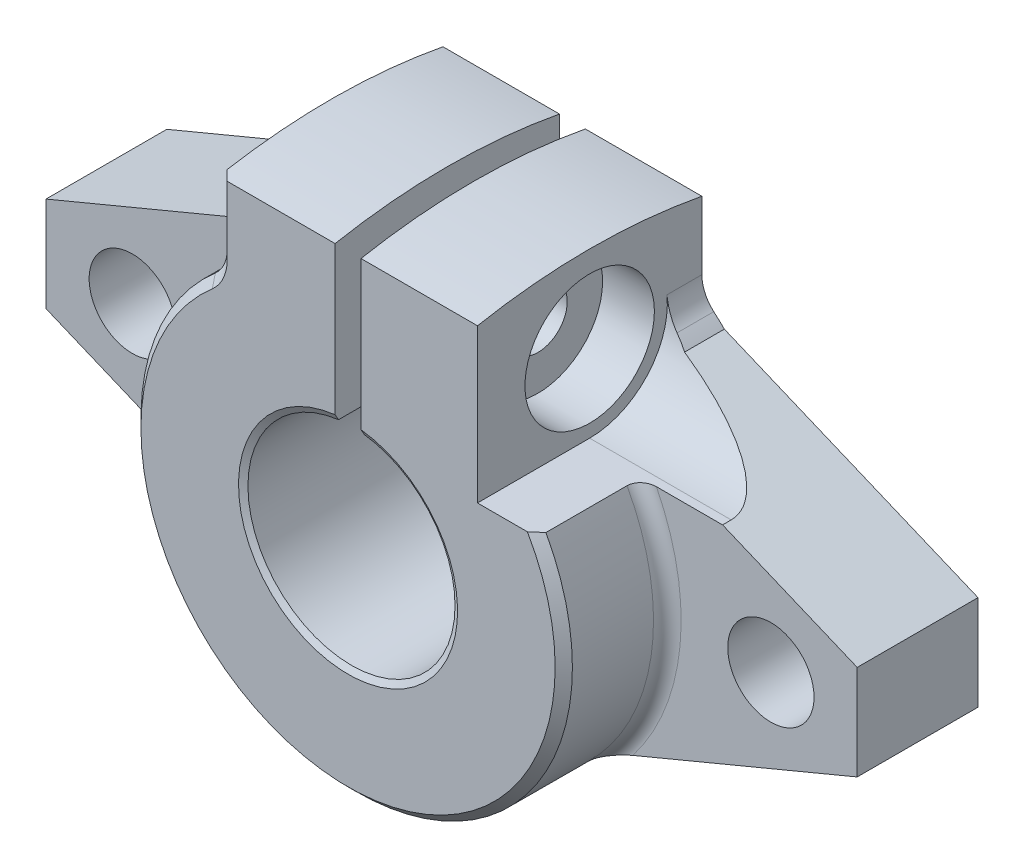
SolidWorks part; units mm, degrees
material "1060 Alloy"
ref_plane "Front Plane" through (0, 0, 0) normal (0, 0, 1) x (1, 0, 0)
ref_plane "Top Plane" through (0, 0, 0) normal (0, 1, 0) x (1, 0, 0)
ref_plane "Right Plane" through (0, 0, 0) normal (1, 0, 0) x (0, 0, -1)
sketch "Sketch1" plane through (0, 0, 0) normal (0, 0, 1) x (1, 0, 0)
  line L0 (0, 23.6454) -> (0, -19.4549) construction
  line L1 (0.75, 5.9529) -> (0.75, 15.5)
  line L2 (0.75, 15.5) -> (7.5, 15.5)
  line L3 (7.5, 15.5) -> (7.5, 10)
  line L4 (-7.5, 15.5) -> (-7.5, 10)
  line L5 (-0.75, 15.5) -> (-7.5, 15.5)
  line L6 (-0.75, 5.9529) -> (-0.75, 15.5)
  arc A0 (-0.75, 5.9529) -> (0.75, 5.9529) centre (0, 0) ccw
  arc A1 (-7.5, 10) -> (7.5, 10) centre (0, 0) ccw
  arc A2 (0, -6) -> (0.818, 5.944) centre (0, 0) ccw construction
  arc A3 (0, -12.5) -> (1.7041, 12.3833) centre (0, 0) ccw construction
  dimension "D1" = 6
  dimension "D3" = 1.5
  dimension "D4" = 15
  dimension "D5" = 28
  dimension "D2" = 6.5
extrude "Boss-Extrude1" add sketch "Sketch1" along normal blind 13
sketch "Sketch2" plane through (0, 0, 0) normal (1, 0, 0) x (0, 0, -1)
  line L0 (0, 10) -> (0, 15.5) construction
  line L1 (-13, 10) -> (-13, 15.5) construction
  line L2 (-6.5, 15.5) -> (-6.5, -4.9716) construction
  line L3 (-13, 15.5) -> (0, 15.5) construction
  arc A0 (0, 14.8911) -> (-13, 14.8911) centre (-6.5, -19.5) ccw
  dimension "D1" = 35
extrude "Cut-Extrude1" cut sketch "Sketch2" against normal through all and the other way through all flip side to cut
fillet "Fillet1" radius 2 2 edges at (-7.5, 10, 6.5) (7.5, 10, 6.5)
sketch "Sketch3" plane through (0, 0, 0) normal (0, 0, 1) x (1, 0, 0)
  line L0 (0, 19.2448) -> (0, 0) construction
  line L1 (0, 0) -> (32.3729, 0) construction
  line L2 (8.8035, 8.874) -> (23.5, 2.75)
  line L3 (23.5, 2.75) -> (23.5, -2.75)
  line L4 (8.8035, -8.874) -> (23.5, -2.75)
  line L5 (-23.5, 2.75) -> (-23.5, -2.75) construction
  arc A0 (-8.1897, 9.4435) -> (8.1897, 9.4435) centre (0, 0) ccw construction
  arc A1 (8.8035, 8.874) -> (8.8035, -8.874) centre (0, 0) cw
  arc A2 (-8.1897, 9.4435) -> (8.1897, 9.4435) centre (0, 0) ccw construction
  point P11 (23.5, 0)
  point P12 (18.5, 0)
  point P15 (-18.5, 0)
  dimension "D1" = 47
  dimension "D2" = 37
  dimension "D3" = 5.5
extrude "Boss-Extrude2" add sketch "Sketch3" along normal blind 7
mirror "Mirror1" about plane through (0, 0, 0) normal (1, 0, 0) of bodies 103
hole_wizard "Диаметр отверстия Ø5.0 (5)1" positions "Sketch5" profile "Sketch4" hole size "Ø5.0" standard "DIN"
sketch "Sketch5" plane through (0, 0, 7) normal (0, 0, 1) x (1, 0, 0)
  point P0 (18.5, 0)
  point P2 (-18.5, 0)
sketch "Sketch4" plane through (18.5, 0, 7) normal (1, 0, 0) x (0, -1, 0)
  line L0 (0, 0) -> (0, 11.5022)
  line L1 (0, 11.5022) -> (2.5, 10)
  line L2 (2.5, 10) -> (2.5, 0)
  line L5 (2.5, 0) -> (0, 0)
  line L10 (0, 11.5022) -> (-2.5, 10) construction
  line L11 (0, -6.35) -> (0, 107.95) construction
  dimension "Диаметр отверстия" = 5
  dimension "Глубина отверстия" = 10
  dimension "Угол заточки сверла" = 118
sketch "Sketch6" plane through (0, 0, 0) normal (1, 0, 0) x (0, 0, -1)
  line L0 (-6.5, -12.5) -> (-6.5, 18.0939) construction
  line L1 (-13, -12.5) -> (0, -12.5) construction
  arc A1 (0, 14.8911) -> (-13, 14.8911) centre (-6.5, -19.5) ccw construction
  point P0 (-6.5, 10.5)
  dimension "D1" = 5
sketch "Sketch9" plane through (7.5, 0, 0) normal (1, 0, 0) x (0, 0, -1)
  line L0 (-6.5, -12.5) -> (-6.5, 18.0939) construction
  line L2 (-13, 10.9545) -> (0, 10.9545) construction
  line L3 (-2.023, 10.9545) -> (-13, 10.9545)
  line L4 (-13, 10.9545) -> (-13, 6)
  line L5 (-13, 9.4435) -> (-13, -12.5) construction
  line L6 (-13, 6) -> (-6.5, 6)
  arc A0 (-6.5, 6) -> (-2.023, 10.9545) centre (-6.5, 10.5) ccw
  dimension "D1" = 4.5
extrude "Cut-Extrude2" cut sketch "Sketch9" along normal up to next
hole_wizard "CBORE for M4 Hex Socket Head Cap Screw3" positions "Sketch11" profile "Sketch10" counterbore size "M4" standard "DIN" end condition through all
sketch "Sketch11" plane through (7.5, 0, 0) normal (1, 0, 0) x (0, 0, -1)
  point P0 (-6.5, 10.5)
sketch "Sketch10" plane through (7.5, 10.5, 6.5) normal (0, 1, 0) x (0, 0, -1)
  line L0 (0, 0) -> (0, 31)
  line L1 (0, 31) -> (1.7, 31)
  line L3 (1.7, 31) -> (1.7, 3)
  line L4 (1.7, 3) -> (3.75, 3)
  line L5 (3.75, 3) -> (3.75, 0)
  line L7 (3.75, 0) -> (0, 0)
  line L11 (0, -6.35) -> (0, 107.95) construction
  dimension "Thru Hole Dia." = 3.4
  dimension "Thru Hole Depth" = 31
  dimension "C'Bore Dia." = 7.5
  dimension "C'Bore Depth" = 3
ref_plane "Plane1" through (0, 0, 6.5) normal (0, 0, 1) x (1, 0, 0)
sketch "Sketch12" plane through (0, 0, 6.5) normal (0, 0, 1) x (1, 0, 0)
  line L0 (0, 10.5) -> (19.7633, 10.5) construction
  line L1 (4.5, 14) -> (8.5, 14)
  line L2 (8.5, 14) -> (8.5, 10.5)
  line L3 (8.5, 10.5) -> (-5.5, 10.5)
  line L4 (-5.5, 10.5) -> (-5.5, 12)
  line L5 (-5.5, 12) -> (-5, 12.5)
  line L6 (-5, 12.5) -> (4.5, 12.5)
  line L7 (4.5, 12.5) -> (4.5, 14)
  line L8 (4.5, 7) -> (8.5, 7) construction
  line L9 (-5, 8.5) -> (4.5, 8.5) construction
  line L10 (4.5, 8.8) -> (4.5, 12.2) construction
  line L11 (4.5, 8.8) -> (4.5, 12.2) construction
  dimension "D1" = 7
  dimension "D2" = 4
  dimension "D3" = 4
  dimension "D4" = 0.5
  dimension "D5" = 10
  dimension "D6" = 45
chamfer "Chamfer2" distance 0.5 angle 45 3 edges at (-7.5, 12.9228, 13) (-7.6806, 10.124, 13) (-2.2116, -12.3028, 13)
fillet "Fillet2" radius 0.8 4 edges at (-12.5, 0, 7) (8.8035, -8.874, 3.5) (-8.8035, -8.874, 3.5) (12.37, -1.7983, 7)
chamfer "Chamfer3" distance 0.2 angle 60 1 edges at (0, -6, 13)
